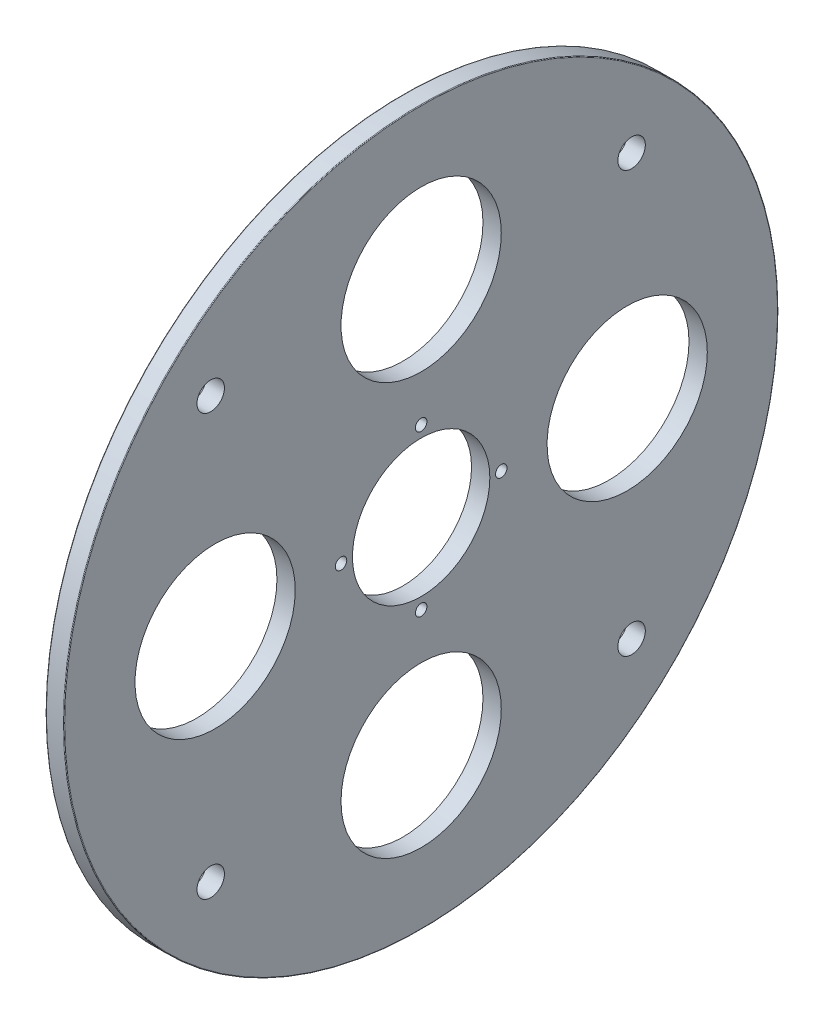
SolidWorks part; units mm, degrees
material "1060 合金"
ref_plane "前视基准面" through (0, 0, 0) normal (0, 0, 1) x (1, 0, 0)
ref_plane "上视基准面" through (0, 0, 0) normal (0, 1, 0) x (1, 0, 0)
ref_plane "右视基准面" through (0, 0, 0) normal (1, 0, 0) x (0, 0, -1)
sketch "草图1" plane through (0, 0, 0) normal (1, 0, 0) x (0, 0, -1)
  circle A0 centre (0, 0) radius 156
extrude "凸台-拉伸1" add sketch "草图1" along normal blind 8
sketch "草图2" plane through (8, 0, 0) normal (1, 0, 0) x (0, 0, -1)
  circle A0 centre (0, 0) radius 30
extrude "切除-拉伸1" cut sketch "草图2" against normal blind 10 contours A0
sketch "草图3" plane through (8, 0, 0) normal (1, 0, 0) x (0, 0, -1)
  circle A0 centre (0, 90) radius 35
extrude "切除-拉伸2" cut sketch "草图3" against normal blind 10 contours A0
pattern_circular "阵列(圆周)1" count 4 over 360 about axis through (0, 0, 0) along (1, 0, 0) of "切除-拉伸2"
sketch "草图4" plane through (8, 0, 0) normal (1, 0, 0) x (0, 0, -1)
  circle A1 centre (91.9239, 91.9239) radius 6
extrude "切除-拉伸3" cut sketch "草图4" against normal blind 10
pattern_circular "阵列(圆周)2" count 4 over 360 about axis through (0, 0, 0) along (1, 0, 0) of "切除-拉伸3"
sketch "草图6" plane through (8, 0, 0) normal (1, 0, 0) x (0, 0, -1)
  circle A0 centre (0, 35) radius 2.5
extrude "切除-拉伸5" cut sketch "草图6" against normal blind 10 contours A0
pattern_circular "阵列(圆周)4" count 4 over 360 about axis through (0, 0, 0) along (1, 0, 0) of "切除-拉伸5"
fillet "圆角1" radius 0.3 2 edges at (0, 0, -156) (8, 0, -156)
